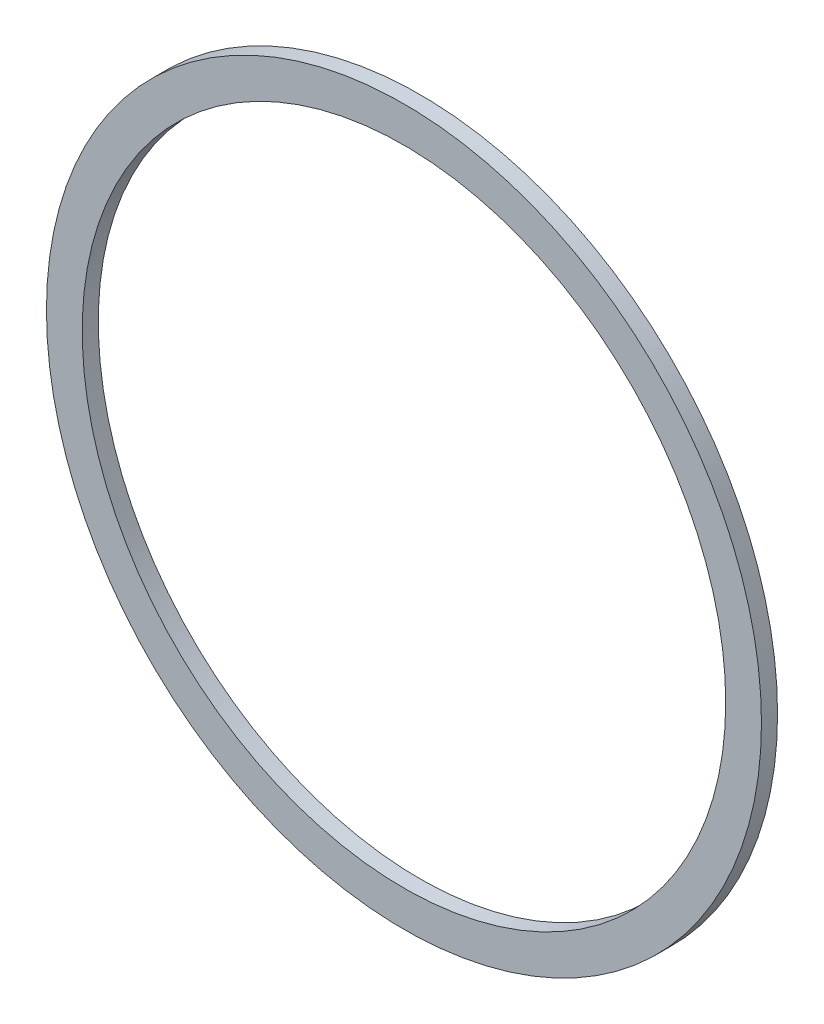
SolidWorks part; units mm, degrees
ref_plane "前视基准面" through (0, 0, 0) normal (0, 0, 1) x (1, 0, 0)
ref_plane "上视基准面" through (0, 0, 0) normal (0, 1, 0) x (1, 0, 0)
ref_plane "右视基准面" through (0, 0, 0) normal (1, 0, 0) x (0, 0, -1)
sketch "草图1" plane through (0, 0, 0) normal (0, 0, 1) x (1, 0, 0)
  circle A0 centre (0, 0) radius 40
  circle A1 centre (0, 0) radius 36
  dimension "D1" = 80
  dimension "D2" = 72
extrude "凸台-拉伸1" add sketch "草图1" along normal blind 1.8
